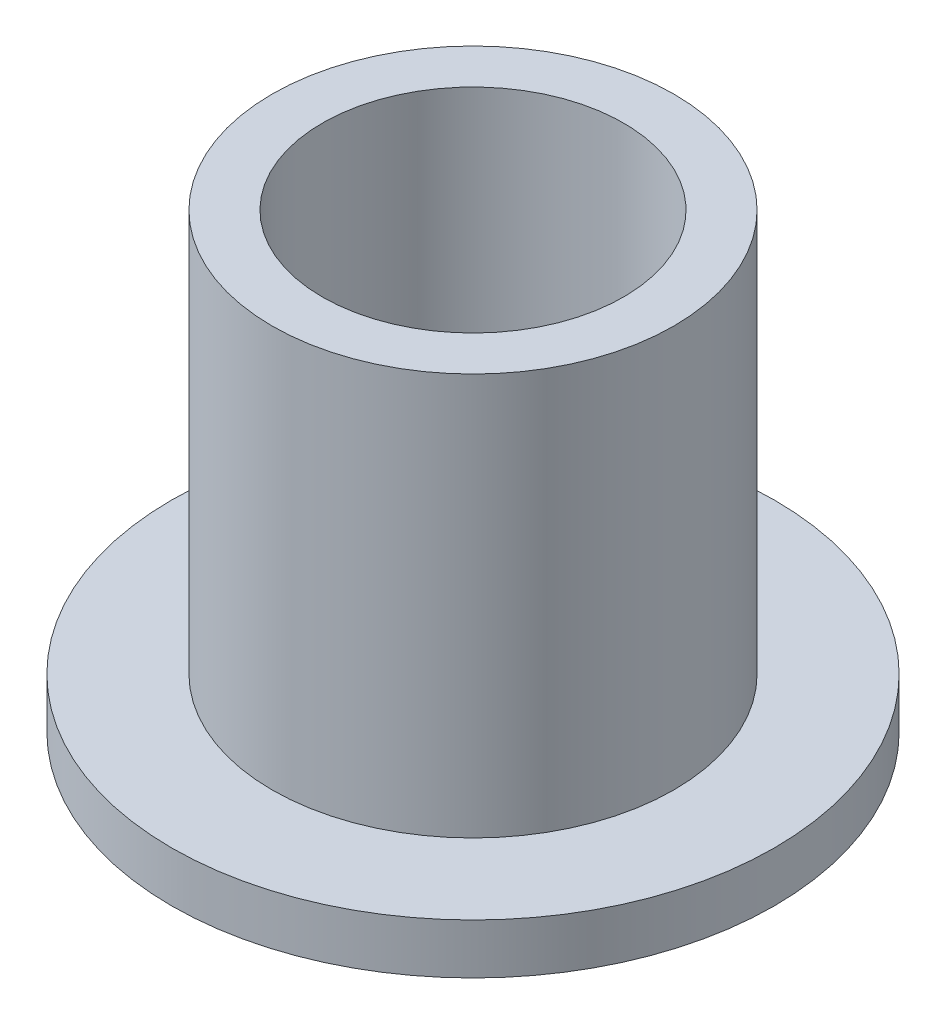
SolidWorks part; units mm, degrees
ref_plane "Front Plane" through (0, 0, 0) normal (0, 0, 1) x (1, 0, 0)
ref_plane "Top Plane" through (0, 0, 0) normal (0, 1, 0) x (1, 0, 0)
ref_plane "Right Plane" through (0, 0, 0) normal (1, 0, 0) x (0, 0, -1)
sketch "Sketch1" plane through (0, 0, 0) normal (0, 1, 0) x (1, 0, 0)
  circle A0 centre (0, 0) radius 3
  circle A1 centre (0, 0) radius 6
extrude "Boss-Extrude1" add sketch "Sketch1" along normal blind 1
sketch "Sketch2" plane through (0, 1, 0) normal (0, 1, 0) x (-1, 0, 0)
  circle A0 centre (0, 0) radius 4
  circle A1 centre (0, 0) radius 3
extrude "Boss-Extrude2" add sketch "Sketch2" along normal blind 8
